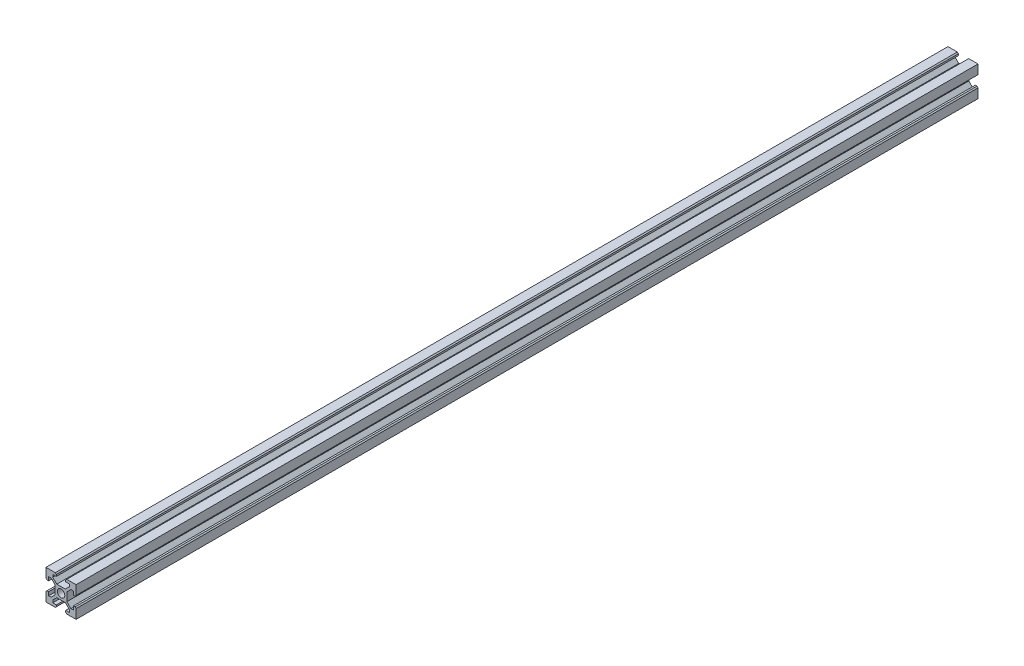
SolidWorks part; units mm, degrees
material "Cast Alloy Steel"
ref_plane "Front Plane" through (0, 0, 0) normal (0, 0, 1) x (1, 0, 0)
ref_plane "Top Plane" through (0, 0, 0) normal (0, 1, 0) x (1, 0, 0)
ref_plane "Right Plane" through (0, 0, 0) normal (1, 0, 0) x (0, 0, -1)
sketch "Sketch1" plane through (0, 0, 0) normal (0, 0, 1) x (1, 0, 0)
  line L0 (3.9, -2.8393) -> (6.5607, -5.5)
  line L1 (-10, 10) -> (10, 10) construction
  line L2 (-10, 10) -> (-10, -10) construction
  line L3 (-10, -10) -> (10, -10) construction
  line L4 (10, 10) -> (10, -10) construction
  line L5 (-10, 10) -> (10, -10) construction
  line L6 (-10, -10) -> (10, 10) construction
  line L7 (-3.9, -3.9) -> (3.9, -3.9) construction
  line L8 (-3.9, -3.9) -> (-3.9, 3.9) construction
  line L9 (-3.9, 3.9) -> (3.9, 3.9) construction
  line L10 (3.9, -3.9) -> (3.9, 3.9) construction
  line L11 (-3.9, -3.9) -> (3.9, 3.9) construction
  line L12 (-3.9, 3.9) -> (3.9, -3.9) construction
  line L13 (-10, 10) -> (-5.5, 10) construction
  line L14 (-10, 10) -> (-10, 5.5) construction
  line L15 (-10, 5.5) -> (-5.5, 5.5) construction
  line L16 (-5.5, 10) -> (-5.5, 5.5) construction
  line L17 (10, 10) -> (5.5, 10) construction
  line L18 (10, 10) -> (10, 5.5) construction
  line L19 (10, 5.5) -> (5.5, 5.5) construction
  line L20 (5.5, 10) -> (5.5, 5.5) construction
  line L21 (-10, -10) -> (-5.5, -10) construction
  line L22 (-10, -10) -> (-10, -5.5) construction
  line L23 (-10, -5.5) -> (-5.5, -5.5) construction
  line L24 (-5.5, -10) -> (-5.5, -5.5) construction
  line L25 (10, -10) -> (5.5, -10) construction
  line L26 (10, -10) -> (10, -5.5) construction
  line L27 (10, -5.5) -> (5.5, -5.5) construction
  line L28 (5.5, -10) -> (5.5, -5.5) construction
  line L29 (2.8393, -3.9) -> (5.5, -6.5607)
  line L30 (-5.5, 6.5607) -> (-2.8393, 3.9)
  line L31 (-6.5607, 5.5) -> (-3.9, 2.8393)
  line L32 (5.5, 6.5607) -> (2.8393, 3.9)
  line L33 (6.5607, 5.5) -> (3.9, 2.8393)
  line L34 (-6.5607, -5.5) -> (-3.9, -2.8393)
  line L35 (-5.5, -6.5607) -> (-2.8393, -3.9)
  line L36 (-2.8393, 3.9) -> (2.8393, 3.9)
  line L37 (-3.9, 2.8393) -> (-3.9, -2.8393)
  line L38 (-2.8393, -3.9) -> (2.8393, -3.9)
  line L39 (3.9, -2.8393) -> (3.9, 2.8393)
  line L40 (5.5, 6.5607) -> (5.5, 8.2007)
  line L41 (5.5, 8.2007) -> (3.1, 8.2007)
  line L42 (3.1, 8.2007) -> (3.1, 9.3)
  line L43 (3.1, 9.3) -> (3.8, 10)
  line L44 (3.8, 10) -> (10, 10)
  line L45 (10, 10) -> (10, 3.8)
  line L46 (10, 3.8) -> (9.3, 3.1)
  line L47 (9.3, 3.1) -> (8.2007, 3.1)
  line L48 (8.2007, 3.1) -> (8.2007, 5.5)
  line L49 (8.2007, 5.5) -> (6.5607, 5.5)
  line L50 (3.1, -8.2007) -> (5.5, -8.2007)
  line L51 (3.1, -9.3) -> (3.1, -8.2007)
  line L52 (3.8, -10) -> (3.1, -9.3)
  line L53 (10, -10) -> (3.8, -10)
  line L54 (10, -3.8) -> (10, -10)
  line L55 (9.3, -3.1) -> (10, -3.8)
  line L56 (8.2007, -3.1) -> (9.3, -3.1)
  line L57 (8.2007, -5.5) -> (8.2007, -3.1)
  line L58 (6.5607, -5.5) -> (8.2007, -5.5)
  line L59 (5.5, -8.2007) -> (5.5, -6.5607)
  line L60 (-8.2007, -3.1) -> (-8.2007, -5.5)
  line L61 (-9.3, -3.1) -> (-8.2007, -3.1)
  line L62 (-10, -3.8) -> (-9.3, -3.1)
  line L63 (-10, -10) -> (-10, -3.8)
  line L64 (-3.8, -10) -> (-10, -10)
  line L65 (-3.1, -9.3) -> (-3.8, -10)
  line L66 (-3.1, -8.2007) -> (-3.1, -9.3)
  line L67 (-5.5, -8.2007) -> (-3.1, -8.2007)
  line L68 (-5.5, -6.5607) -> (-5.5, -8.2007)
  line L69 (-8.2007, -5.5) -> (-6.5607, -5.5)
  line L70 (-3.1, 8.2007) -> (-5.5, 8.2007)
  line L71 (-3.1, 9.3) -> (-3.1, 8.2007)
  line L72 (-3.8, 10) -> (-3.1, 9.3)
  line L73 (-10, 10) -> (-3.8, 10)
  line L74 (-10, 3.8) -> (-10, 10)
  line L75 (-9.3, 3.1) -> (-10, 3.8)
  line L76 (-8.2007, 3.1) -> (-9.3, 3.1)
  line L77 (-8.2007, 5.5) -> (-8.2007, 3.1)
  line L78 (-6.5607, 5.5) -> (-8.2007, 5.5)
  line L79 (-5.5, 8.2007) -> (-5.5, 6.5607)
  circle A0 centre (0, 0) radius 2.5
  point P83 (0, 0)
  dimension "D1" = 5
  dimension "D2" = 20
  dimension "D3" = 7.8
  dimension "D4" = 4.5
  dimension "D5" = 1.5
  dimension "D6" = 0.75
  dimension "D7" = 1.5
  dimension "D8" = 0.75
  dimension "D9" = 1.5
  dimension "D10" = 0.75
  dimension "D11" = 1.5
  dimension "D12" = 0.75
  dimension "D13" = 1.64
  dimension "D14" = 45
  dimension "D15" = 3.1
  dimension "D16" = 6.2
  dimension "D17" = 6.2
  dimension "D18" = 3.1
  dimension "D19" = 4
extrude "Boss-Extrude1" add sketch "Sketch1" along normal mid plane 600 contours L79 L70 L71 L72 L73 L74 L75 L76 L77 L78 L31 L37 L34 L69 L60 L61 L62 L63 L64 L65 L66 L67 L68 L35 L38 L29 L59 L50 L51 L52 L53 L54 L55 L56 L57 L58 L0 L39 L33 L49 L48 L47 L46 L45 L44 L43 L42 L41 L40 L32 L36
